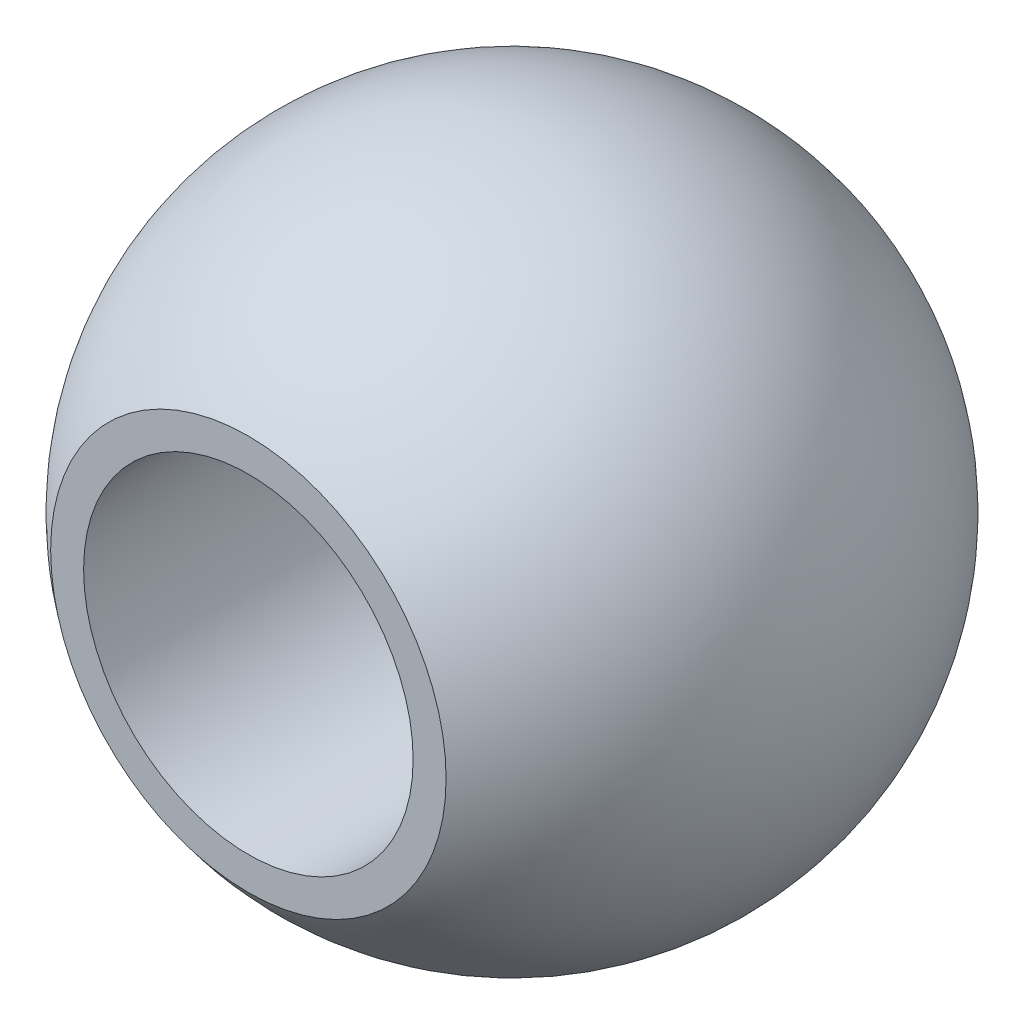
SolidWorks part; units mm, degrees
ref_plane "Front Plane" through (0, 0, 0) normal (0, 0, 1) x (1, 0, 0)
ref_plane "Top Plane" through (0, 0, 0) normal (0, 1, 0) x (1, 0, 0)
ref_plane "Right Plane" through (0, 0, 0) normal (1, 0, 0) x (0, 0, -1)
sketch "Sketch2" plane through (0, 0, 0) normal (1, 0, 0) x (0, 0, -1)
  line L0 (0, 0) -> (0, 8.1733) construction
  line L1 (0, 0) -> (0, -5) construction
  line L2 (10, 0) -> (-10.56, 0) construction
  line L4 (-4, 7.5) -> (4, 7.5)
  line L5 (-4, 7.5) -> (-4, 2.5)
  line L6 (-4, 2.5) -> (4, 2.5)
  line L7 (4, 7.5) -> (4, 2.5)
  circle A0 centre (0, 0) radius 5
  point P13 (0, -2.5)
  dimension "D4" = 10
  dimension "D1" = 8
  dimension "D2" = 5
  dimension "D5" = 5
revolve "Revolve2" add sketch "Sketch2" angle 360 about L2
